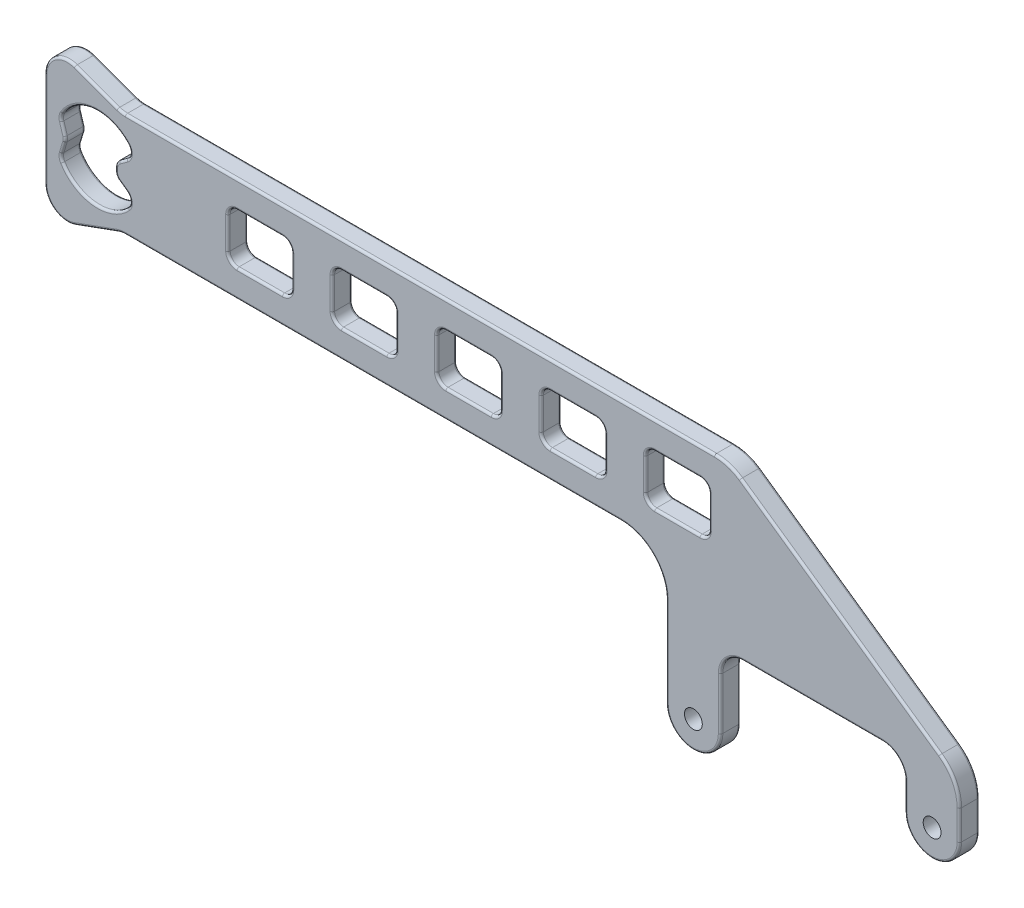
SolidWorks part; units mm, degrees
other "Markup1"
sketch "Sketch10" plane through (-231.7542, 109.3418, 2.54) normal (-0.196, 0.5701, 0.7978) x (0.8612, -0.289, 0.4181)
sketch "Sketch12" plane through (-223.9721, 110.3689, 5.588) normal (-0.196, 0.5701, 0.7978) x (0.8612, -0.289, 0.4181)
material "Alloy Steel"
ref_plane "Front Plane" through (0, 0, 0) normal (0, 0, 1) x (1, 0, 0)
ref_plane "Top Plane" through (0, 0, 0) normal (0, 1, 0) x (1, 0, 0)
ref_plane "Right Plane" through (0, 0, 0) normal (1, 0, 0) x (0, 0, -1)
sketch "Sketch1" plane through (0, 0, 0) normal (0, 0, 1) x (1, 0, 0)
  line L0 (-51.1821, 45.104) -> (-51.1821, 70.2222)
  line L1 (-225.0635, 110.882) -> (-225.0635, 84.1724)
  line L2 (15.625, 52.2091) -> (15.625, 59.6953)
  line L3 (-204.6342, 112.5152) -> (-216.5416, 116.8491)
  line L4 (24.515, 112.1322) -> (-202.4624, 112.1322)
  line L5 (-202.4624, 82.9222) -> (-63.8821, 82.9222)
  line L6 (-35.9421, 45.104) -> (-35.9421, 59.6953)
  line L7 (-29.5921, 66.0453) -> (9.275, 66.0453)
  line L8 (-204.6342, 82.5393) -> (-216.5416, 78.2053)
  line L9 (-203.5821, 112.1322) -> (-203.5821, 82.9222) construction
  line L10 (30.865, 52.2091) -> (30.865, 105.7822)
  circle A0 centre (-43.5621, 45.104) radius 2.5 construction
  circle A1 centre (-43.5621, 45.104) radius 2.5
  circle A2 centre (23.245, 52.2091) radius 2.5 construction
  circle A3 centre (23.245, 52.2091) radius 2.5
  circle A4 centre (-43.5621, 45.104) radius 7.62
  circle A5 centre (23.245, 52.2091) radius 7.62
  arc A6 (-51.1821, 70.2222) -> (-63.8821, 82.9222) centre (-63.8821, 70.2222) ccw
  arc A10 (30.865, 105.7822) -> (24.515, 112.1322) centre (24.515, 105.7822) ccw
  arc A11 (-202.4624, 112.1322) -> (-204.6342, 112.5152) centre (-202.4624, 118.4822) cw
  arc A14 (15.625, 59.6953) -> (9.275, 66.0453) centre (9.275, 59.6953) ccw
  arc A15 (-29.5921, 66.0453) -> (-35.9421, 59.6953) centre (-29.5921, 59.6953) ccw
  arc A16 (-202.4624, 82.9222) -> (-204.6342, 82.5393) centre (-202.4624, 76.5722) ccw
  arc A17 (-216.5416, 78.2053) -> (-225.0635, 84.1724) centre (-218.7135, 84.1724) cw
  arc A18 (-216.5416, 116.8491) -> (-225.0635, 110.882) centre (-218.7135, 110.882) ccw
  point P37 (32.653, 69.7785)
  point P40 (-225.0635, 119.9508)
  dimension "D1" = 15.24
  dimension "D2" = 12.7
  dimension "D5" = 20
  dimension "D6" = 22.86
  dimension "D7" = 139.7
  dimension "D8" = 6.35
  dimension "D3" = 6.35
  dimension "D4" = 29.21
  dimension "D10" = 6.35
  dimension "D9" = 20
sketch "Sketch9" plane through (0, 0, 0) normal (0, 0, 1) x (1, 0, 0)
  line L0 (-200.3986, 101.5627) -> (-206.3477, 98.901)
  line L1 (-230.8813, 109.1826) -> (-231.1891, 107.025)
  line L2 (-231.0352, 108.1038) -> (-31.7302, 79.671) construction
  line L3 (-204.7592, 110.0362) -> (-174.8282, 105.7663) construction
  line L4 (-190.5732, 97.9876) -> (-182.1974, 90.8738)
  line L5 (-182.2147, 103.3096) -> (-176.2656, 105.9713)
  line L6 (-178.6469, 115.7616) -> (-182.5307, 88.5377) construction
  line L20 (-200.4159, 113.9985) -> (-179.3276, 110.9901)
  line L21 (-204.7592, 110.0362) -> (-206.3477, 98.901)
  line L22 (-176.2656, 105.9713) -> (-177.8541, 94.8361)
  line L23 (-203.2857, 93.8822) -> (-182.1974, 90.8738)
  line L24 (-171.3421, 113.5062) -> (-175.2234, 86.2993) construction
  line L29 (-136.2614, 108.4187) -> (-140.1311, 81.293) construction
  line L34 (-99.6701, 103.0287) -> (-103.5282, 75.9843) construction
  line L39 (-62.2356, 97.6053) -> (-66.0821, 70.6423) construction
  line L44 (-204.7592, 110.0362) -> (-199.7917, 105.8172)
  line L45 (-200.4159, 113.9985) -> (-192.0401, 106.8847)
  line L46 (-179.3276, 110.9901) -> (-189.3585, 106.5022)
  line L47 (-203.2857, 93.8822) -> (-193.2548, 98.3701)
  line L48 (-182.8216, 99.0551) -> (-177.8541, 94.8361)
  line L49 (-163.7544, 100.6761) -> (-168.7219, 104.8952)
  line L50 (-164.3614, 96.4216) -> (-170.3105, 93.7599)
  line L51 (-157.2176, 93.2291) -> (-167.2484, 88.7411)
  line L52 (-146.1602, 85.7327) -> (-154.5359, 92.8465)
  line L53 (-146.7844, 93.9141) -> (-141.8169, 89.695)
  line L54 (-140.2283, 100.8303) -> (-146.1774, 98.1685)
  line L55 (-143.2904, 105.849) -> (-153.3213, 101.3611)
  line L56 (-164.3786, 108.8575) -> (-156.0029, 101.7437)
  line L57 (-146.1602, 85.7327) -> (-167.2484, 88.7411)
  line L58 (-140.2283, 100.8303) -> (-141.8169, 89.695)
  line L59 (-143.2904, 105.849) -> (-164.3786, 108.8575)
  line L60 (-168.7219, 104.8952) -> (-170.3105, 93.7599)
  line L61 (-133.1011, 83.8697) -> (-112.0129, 80.8612)
  line L62 (-120.3887, 87.9751) -> (-112.0129, 80.8612)
  line L63 (-133.1011, 83.8697) -> (-123.0703, 88.3576)
  line L64 (-134.5746, 100.0237) -> (-136.1632, 88.8884)
  line L65 (-134.5746, 100.0237) -> (-129.6071, 95.8046)
  line L66 (-130.2141, 91.5502) -> (-136.1632, 88.8884)
  line L67 (-112.6371, 89.0426) -> (-107.6696, 84.8235)
  line L68 (-106.081, 95.9588) -> (-107.6696, 84.8235)
  line L69 (-112.0301, 93.2971) -> (-106.081, 95.9588)
  line L70 (-109.1431, 100.9776) -> (-119.174, 96.4896)
  line L71 (-130.2313, 103.986) -> (-109.1431, 100.9776)
  line L72 (-130.2313, 103.986) -> (-121.8556, 96.8722)
  line L73 (-72.93, 75.2857) -> (-94.0183, 78.2941)
  line L74 (-72.93, 75.2857) -> (-81.3058, 82.3995)
  line L75 (-83.9874, 82.782) -> (-94.0183, 78.2941)
  line L76 (-91.1312, 85.9746) -> (-97.0803, 83.3129)
  line L77 (-95.4918, 94.4481) -> (-97.0803, 83.3129)
  line L78 (-73.5542, 83.4671) -> (-68.5867, 79.248)
  line L79 (-66.9982, 90.3832) -> (-68.5867, 79.248)
  line L80 (-66.9982, 90.3832) -> (-72.9473, 87.7215)
  line L81 (-70.0602, 95.402) -> (-80.0911, 90.9141)
  line L82 (-91.1485, 98.4105) -> (-82.7727, 91.2966)
  line L83 (-70.0602, 95.402) -> (-91.1485, 98.4105)
  line L84 (-90.5243, 90.2291) -> (-95.4918, 94.4481)
  line L85 (-55.322, 80.866) -> (-61.2711, 78.2043)
  line L86 (-59.6825, 89.3396) -> (-54.715, 85.1205)
  line L87 (-55.3392, 93.3019) -> (-46.9635, 86.1881)
  line L88 (-34.251, 90.2935) -> (-44.2818, 85.8055)
  line L89 (-37.138, 82.613) -> (-31.1889, 85.2747)
  line L90 (-37.745, 78.3585) -> (-32.7775, 74.1394)
  line L91 (-45.4965, 77.2909) -> (-37.1208, 70.1771)
  line L92 (-58.209, 73.1856) -> (-48.1781, 77.6735)
  line L93 (-58.209, 73.1856) -> (-37.1208, 70.1771)
  line L94 (-59.6825, 89.3396) -> (-61.2711, 78.2043)
  line L95 (-55.3392, 93.3019) -> (-34.251, 90.2935)
  line L96 (-31.1889, 85.2747) -> (-32.7775, 74.1394)
  arc A0 (-200.4159, 113.9985) -> (-204.7592, 110.0362) centre (-200.954, 110.2267) ccw
  arc A1 (-179.3276, 110.9901) -> (-176.2656, 105.9713) centre (-179.8657, 107.2183) cw
  arc A2 (-182.1974, 90.8738) -> (-177.8541, 94.8361) centre (-181.6594, 94.6456) ccw
  arc A3 (-203.2857, 93.8822) -> (-206.3477, 98.901) centre (-202.7476, 97.654) cw
  arc A20 (-190.5732, 97.9876) -> (-193.2548, 98.3701) centre (-192.2175, 96.0516) ccw
  arc A21 (-200.3986, 101.5627) -> (-199.7917, 105.8172) centre (-201.436, 103.8812) ccw
  arc A22 (-182.8216, 99.0551) -> (-182.2147, 103.3096) centre (-181.1773, 100.9911) cw
  arc A23 (-192.0401, 106.8847) -> (-189.3585, 106.5022) centre (-190.3958, 108.8207) ccw
  arc A24 (-164.3614, 96.4216) -> (-163.7544, 100.6761) centre (-165.3987, 98.7401) ccw
  arc A25 (-157.2176, 93.2291) -> (-154.5359, 92.8465) centre (-156.1802, 90.9105) cw
  arc A26 (-146.7844, 93.9141) -> (-146.1774, 98.1685) centre (-145.1401, 95.85) cw
  arc A27 (-153.3213, 101.3611) -> (-156.0029, 101.7437) centre (-154.3586, 103.6796) cw
  arc A28 (-146.1602, 85.7327) -> (-141.8169, 89.695) centre (-145.6221, 89.5045) ccw
  arc A29 (-143.2904, 105.849) -> (-140.2283, 100.8303) centre (-143.8285, 102.0772) cw
  arc A30 (-164.3786, 108.8575) -> (-168.7219, 104.8952) centre (-164.9167, 105.0857) ccw
  arc A31 (-167.2484, 88.7411) -> (-170.3105, 93.7599) centre (-166.7103, 92.5129) cw
  arc A32 (-112.0129, 80.8612) -> (-107.6696, 84.8235) centre (-111.4748, 84.633) ccw
  arc A33 (-120.3887, 87.9751) -> (-123.0703, 88.3576) centre (-122.0329, 86.0391) ccw
  arc A34 (-133.1011, 83.8697) -> (-136.1632, 88.8884) centre (-132.563, 87.6415) cw
  arc A35 (-130.2141, 91.5502) -> (-129.6071, 95.8046) centre (-131.2514, 93.8687) ccw
  arc A36 (-112.6371, 89.0426) -> (-112.0301, 93.2971) centre (-110.9928, 90.9786) cw
  arc A37 (-109.1431, 100.9776) -> (-106.081, 95.9588) centre (-109.6812, 97.2058) cw
  arc A38 (-121.8556, 96.8722) -> (-119.174, 96.4896) centre (-120.2113, 98.8082) ccw
  arc A39 (-130.2313, 103.986) -> (-134.5746, 100.0237) centre (-130.7694, 100.2142) ccw
  arc A40 (-72.93, 75.2857) -> (-68.5867, 79.248) centre (-72.392, 79.0575) ccw
  arc A41 (-83.9874, 82.782) -> (-81.3058, 82.3995) centre (-82.9501, 80.4635) cw
  arc A42 (-94.0183, 78.2941) -> (-97.0803, 83.3129) centre (-93.4802, 82.0659) cw
  arc A43 (-91.1312, 85.9746) -> (-90.5243, 90.2291) centre (-92.1686, 88.2931) ccw
  arc A44 (-73.5542, 83.4671) -> (-72.9473, 87.7215) centre (-71.9099, 85.403) cw
  arc A45 (-70.0602, 95.402) -> (-66.9982, 90.3832) centre (-70.5983, 91.6302) cw
  arc A46 (-80.0911, 90.9141) -> (-82.7727, 91.2966) centre (-81.1284, 93.2326) cw
  arc A47 (-91.1485, 98.4105) -> (-95.4918, 94.4481) centre (-91.6866, 94.6386) ccw
  arc A48 (-55.322, 80.866) -> (-54.715, 85.1205) centre (-56.3593, 83.1846) ccw
  arc A49 (-46.9635, 86.1881) -> (-44.2818, 85.8055) centre (-45.3192, 88.1241) ccw
  arc A50 (-37.745, 78.3585) -> (-37.138, 82.613) centre (-36.1007, 80.2945) cw
  arc A51 (-37.1208, 70.1771) -> (-32.7775, 74.1394) centre (-36.5827, 73.9489) ccw
  arc A52 (-45.4965, 77.2909) -> (-48.1781, 77.6735) centre (-47.1408, 75.355) ccw
  arc A53 (-58.209, 73.1856) -> (-61.2711, 78.2043) centre (-57.6709, 76.9574) cw
  arc A54 (-55.3392, 93.3019) -> (-59.6825, 89.3396) centre (-55.8773, 89.5301) ccw
  arc A55 (-34.251, 90.2935) -> (-31.1889, 85.2747) centre (-34.7891, 86.5216) cw
  point P23 (-177.0598, 100.4037)
  point P24 (-205.5535, 104.4686)
  point P85 (-196.7202, 103.2084)
  point P88 (-185.8931, 101.6639)
  dimension "D2" = 3.81
  dimension "D3" = 3.81
  dimension "D8" = 2.54
  dimension "D1" = 10.16
  dimension "D4" = 3.81
extrude "Boss-Extrude1" add sketch "Sketch1" along normal blind 5.588
sketch "Sketch11" plane through (0, 0, 5.588) normal (0, 0, 1) x (1, 0, 0)
  line L0 (-225.0635, 97.5272) -> (-181.5504, 97.5272) construction
  line L1 (-225.0635, 110.882) -> (-225.0635, 84.1724) construction
  line L10 (-202.2175, 93.6173) -> (-204.2535, 95.0676)
  line L11 (-202.2086, 101.4361) -> (-204.241, 99.981)
  line L12 (-205.3018, 97.9722) -> (-205.3191, 97.1929)
  line L13 (-200.1771, 112.1322) -> (-200.1771, 82.9222) construction
  line L14 (24.515, 112.1322) -> (-202.4624, 112.1322) construction
  line L15 (-202.4624, 82.9222) -> (-63.8821, 82.9222) construction
  line L16 (-219.3537, 96.78) -> (-220.3082, 93.6789)
  line L17 (-219.3537, 98.2744) -> (-220.3082, 101.3755)
  arc A5 (-201.8062, 105.2083) -> (-220.0549, 103.4358) centre (-210.2706, 97.5272) ccw
  arc A8 (-201.8114, 89.8404) -> (-202.2175, 93.6173) centre (-203.6912, 91.5486) ccw
  arc A9 (-204.2535, 95.0676) -> (-205.3191, 97.1929) centre (-202.7797, 97.1364) cw
  arc A10 (-204.241, 99.981) -> (-205.3018, 97.9722) centre (-202.7624, 97.9157) ccw
  arc A11 (-201.8062, 105.2083) -> (-202.2086, 101.4361) centre (-203.6872, 103.5014) cw
  arc A12 (-220.0549, 91.6186) -> (-201.8114, 89.8404) centre (-210.2706, 97.5272) ccw
  arc A13 (-219.3537, 98.2744) -> (-219.3537, 96.78) centre (-221.7813, 97.5272) cw
  arc A14 (-220.0549, 91.6186) -> (-220.3082, 93.6789) centre (-217.8806, 92.9316) cw
  arc A15 (-220.0549, 103.4358) -> (-220.3082, 101.3755) centre (-217.8806, 102.1228) ccw
  point P11 (-206.719, 87.8213)
  point P14 (-210.1269, 97.5272)
  point P20 (-200.1771, 92.1638)
  point P23 (-205.349, 95.8481)
  point P28 (-200.1771, 102.8906)
  point P33 (-219.1237, 97.5272)
  point P36 (-220.6182, 92.672)
  dimension "D1" = 22.86
  dimension "D2" = 6.35
  dimension "D3" = 2.54
  dimension "D4" = 5.08
  dimension "D5" = 2.54
extrude "Cut-Extrude1" cut sketch "Sketch11" against normal up to next
sketch "Sketch13" plane through (0, 0, 5.588) normal (0, 0, 1) x (1, 0, 0)
  line L0 (-12.6964, 112.1322) -> (30.865, 67.1311)
  line L1 (24.515, 112.1322) -> (-202.4624, 112.1322) construction
  line L2 (30.865, 52.2091) -> (30.865, 105.7822) construction
  line L3 (30.865, 67.1311) -> (30.865, 105.7822)
  line L4 (24.515, 112.1322) -> (-12.6964, 112.1322)
  arc A0 (30.865, 105.7822) -> (24.515, 112.1322) centre (24.515, 105.7822) ccw construction
  arc A1 (30.865, 105.7822) -> (24.515, 112.1322) centre (24.515, 105.7822) ccw
sketch "Sketch14" plane through (0, 0, 5.588) normal (0, 0, 1) x (1, 0, 0)
  line L0 (-173.7796, 101.9722) -> (-173.7796, 93.0822)
  line L1 (-171.2396, 90.5422) -> (-158.5396, 90.5422)
  line L2 (-155.9996, 93.0822) -> (-155.9996, 101.9722)
  line L3 (-158.5396, 104.5122) -> (-171.2396, 104.5122)
  line L12 (-202.4624, 82.9222) -> (-63.8821, 82.9222) construction
  line L13 (24.515, 112.1322) -> (-202.4624, 112.1322) construction
  line L14 (-144.5696, 101.9722) -> (-144.5696, 93.0822)
  line L15 (-142.0296, 90.5422) -> (-129.3296, 90.5422)
  line L16 (-126.7896, 93.0822) -> (-126.7896, 101.9722)
  line L17 (-129.3296, 104.5122) -> (-142.0296, 104.5122)
  line L18 (-115.3596, 101.9722) -> (-115.3596, 93.0822)
  line L19 (-112.8196, 90.5422) -> (-100.1196, 90.5422)
  line L20 (-97.5796, 93.0822) -> (-97.5796, 101.9722)
  line L21 (-100.1196, 104.5122) -> (-112.8196, 104.5122)
  line L30 (-86.1496, 101.9722) -> (-86.1496, 93.0822)
  line L31 (-83.6096, 90.5422) -> (-70.9096, 90.5422)
  line L32 (-68.3696, 93.0822) -> (-68.3696, 101.9722)
  line L33 (-70.9096, 104.5122) -> (-83.6096, 104.5122)
  line L34 (-56.9396, 101.9722) -> (-56.9396, 93.0822)
  line L35 (-54.3996, 90.5422) -> (-41.6996, 90.5422)
  line L36 (-39.1596, 93.0822) -> (-39.1596, 101.9722)
  line L37 (-41.6996, 104.5122) -> (-54.3996, 104.5122)
  arc A0 (-155.9996, 101.9722) -> (-158.5396, 104.5122) centre (-158.5396, 101.9722) ccw
  arc A1 (-155.9996, 93.0822) -> (-158.5396, 90.5422) centre (-158.5396, 93.0822) cw
  arc A2 (-171.2396, 90.5422) -> (-173.7796, 93.0822) centre (-171.2396, 93.0822) cw
  arc A3 (-171.2396, 104.5122) -> (-173.7796, 101.9722) centre (-171.2396, 101.9722) ccw
  arc A8 (-126.7896, 101.9722) -> (-129.3296, 104.5122) centre (-129.3296, 101.9722) ccw
  arc A9 (-126.7896, 93.0822) -> (-129.3296, 90.5422) centre (-129.3296, 93.0822) cw
  arc A10 (-142.0296, 90.5422) -> (-144.5696, 93.0822) centre (-142.0296, 93.0822) cw
  arc A11 (-142.0296, 104.5122) -> (-144.5696, 101.9722) centre (-142.0296, 101.9722) ccw
  arc A12 (-97.5796, 101.9722) -> (-100.1196, 104.5122) centre (-100.1196, 101.9722) ccw
  arc A13 (-97.5796, 93.0822) -> (-100.1196, 90.5422) centre (-100.1196, 93.0822) cw
  arc A14 (-112.8196, 90.5422) -> (-115.3596, 93.0822) centre (-112.8196, 93.0822) cw
  arc A15 (-112.8196, 104.5122) -> (-115.3596, 101.9722) centre (-112.8196, 101.9722) ccw
  arc A24 (-68.3696, 101.9722) -> (-70.9096, 104.5122) centre (-70.9096, 101.9722) ccw
  arc A25 (-68.3696, 93.0822) -> (-70.9096, 90.5422) centre (-70.9096, 93.0822) cw
  arc A26 (-83.6096, 90.5422) -> (-86.1496, 93.0822) centre (-83.6096, 93.0822) cw
  arc A27 (-83.6096, 104.5122) -> (-86.1496, 101.9722) centre (-83.6096, 101.9722) ccw
  arc A28 (-39.1596, 101.9722) -> (-41.6996, 104.5122) centre (-41.6996, 101.9722) ccw
  arc A29 (-39.1596, 93.0822) -> (-41.6996, 90.5422) centre (-41.6996, 93.0822) cw
  arc A30 (-54.3996, 90.5422) -> (-56.9396, 93.0822) centre (-54.3996, 93.0822) cw
  arc A31 (-54.3996, 104.5122) -> (-56.9396, 101.9722) centre (-54.3996, 101.9722) ccw
  point P28 (-155.6592, 95.109)
  dimension "D1" = 2.54
  dimension "D2" = 7.62
  dimension "D3" = 7.62
  dimension "D4" = 7.62
  dimension "D5" = 7.62
  dimension "D6" = 11.43
  dimension "D7" = 11.43
  dimension "D8" = 7.62
  dimension "D9" = 7.62
  dimension "D10" = 7.62
  dimension "D11" = 7.62
  dimension "D12" = 11.43
  dimension "D13" = 12.7
  dimension "D14" = 12.7
  dimension "D15" = 7.62
  dimension "D16" = 11.43
extrude "Cut-Extrude3" cut sketch "Sketch14" against normal up to next
sketch "Sketch17" plane through (0, 0, 5.588) normal (0, 0, 1) x (1, 0, 0)
  line L0 (-33.6457, 112.1322) -> (30.865, 67.1311)
  line L1 (24.515, 112.1322) -> (-202.4624, 112.1322) construction
  line L2 (30.865, 67.1311) -> (30.865, 105.7822) construction
  line L3 (30.865, 67.1311) -> (30.865, 105.7822)
  line L4 (24.515, 112.1322) -> (-33.6457, 112.1322)
  arc A0 (30.865, 105.7822) -> (24.515, 112.1322) centre (24.515, 105.7822) ccw construction
  arc A1 (30.865, 105.7822) -> (24.515, 112.1322) centre (24.515, 105.7822) ccw
extrude "Cut-Extrude5" cut sketch "Sketch17" against normal up to next
fillet "Fillet3" radius 12.7 2 edges at (30.865, 67.1311, 2.794) (-33.6457, 112.1322, 2.794)
fillet "Fillet5" radius 0.635 115 edges at (-203.5651, 112.2287, 0) (-222.3557, 116.0837, 0) (-222.3557, 78.9707, 0) (-210.5879, 80.3723, 0) (-203.5651, 82.8257, 0) (-133.1723, 82.9222, 0) (-54.9018, 79.2025, 0) (-35.9421, 52.3997, 0) (-34.0822, 64.1854, 0) (-10.1585, 66.0453, 0) (13.7651, 64.1854, 0) (15.625, 55.9522, 0) (23.245, 44.5891, 0) (30.865, 56.3574, 0) (29.4248, 66.3798, 0) (-2.4703, 90.385, 0) (-33.8294, 111.5478, 0) (-120.05, 112.1322, 0) (-211.3756, 108.9037, 0) (-201.1615, 103.232, 0) (-203.2248, 100.7086, 0) (-205.0085, 99.1018, 0) (-205.0503, 95.9979, 0) (-203.2355, 94.3425, 0) (-201.1658, 91.8201, 0) (-220.4017, 92.6217, 0) (-219.831, 95.2294, 0) (-219.2413, 97.5272, 0) (-219.831, 99.825, 0) (-126.7896, 97.5272, 0) (-127.5335, 91.2862, 0) (-135.6796, 90.5422, 0) (-143.8256, 91.2862, 0) (-143.8256, 103.7683, 0) (-135.6796, 104.5122, 0) (-127.5335, 103.7683, 0) (-156.7435, 91.2862, 0) (-164.8896, 90.5422, 0) (-173.7796, 97.5272, 0) (-173.0356, 103.7683, 0) (-164.8896, 104.5122, 0) (-155.9996, 97.5272, 0) (-98.3235, 103.7683, 0) (-98.3235, 91.2862, 0) (-106.4696, 90.5422, 0) (-114.6156, 91.2862, 0) (-115.3596, 97.5272, 0) (-69.1135, 103.7683, 0) (-68.3696, 97.5272, 0) (-85.4056, 91.2862, 0) (-86.1496, 97.5272, 0) (-85.4056, 103.7683, 0) (-77.2596, 104.5122, 0) (-39.9035, 103.7683, 0) (-39.1596, 97.5272, 0) (-48.0496, 90.5422, 0) (-56.1956, 91.2862, 0) (-56.9396, 97.5272, 0) (-56.1956, 103.7683, 0) (-220.4017, 92.6217, 5.588) (-211.3794, 86.1511, 5.588) (-201.1658, 91.8201, 5.588) (-205.0503, 95.9979, 5.588) (-205.3105, 97.5825, 5.588) (-205.0085, 99.1018, 5.588) (-203.2248, 100.7086, 5.588) (-201.1615, 103.232, 5.588) (-219.831, 99.825, 5.588) (-219.2413, 97.5272, 5.588) (-143.8256, 103.7683, 5.588) (-144.5696, 97.5272, 5.588) (-135.6796, 90.5422, 5.588) (-127.5335, 91.2862, 5.588) (-126.7896, 97.5272, 5.588) (-127.5335, 103.7683, 5.588) (-135.6796, 104.5122, 5.588) (-164.8896, 104.5122, 5.588) (-173.0356, 103.7683, 5.588) (-173.7796, 97.5272, 5.588) (-173.0356, 91.2862, 5.588) (-164.8896, 90.5422, 5.588) (-156.7435, 91.2862, 5.588) (-155.9996, 97.5272, 5.588) (-106.4696, 90.5422, 5.588) (-97.5796, 97.5272, 5.588) (-98.3235, 103.7683, 5.588) (-114.6156, 103.7683, 5.588) (-85.4056, 91.2862, 5.588) (-77.2596, 90.5422, 5.588) (-69.1135, 91.2862, 5.588) (-68.3696, 97.5272, 5.588) (-77.2596, 104.5122, 5.588) (-85.4056, 103.7683, 5.588) (-56.9396, 97.5272, 5.588) (-56.1956, 91.2862, 5.588) (-39.9035, 91.2862, 5.588) (-39.1596, 97.5272, 5.588) (-39.9035, 103.7683, 5.588) (-48.0496, 104.5122, 5.588) (-56.1956, 103.7683, 5.588) (29.4248, 66.3798, 5.588) (30.865, 56.3574, 5.588) (-10.1585, 66.0453, 5.588) (-35.9421, 52.3997, 5.588) (-54.9018, 79.2025, 5.588) (-133.1723, 82.9222, 5.588) (-210.5879, 80.3723, 5.588) (-222.3557, 78.9707, 5.588) (-225.0635, 97.5272, 5.588) (-222.3557, 116.0837, 5.588) (-210.5879, 114.6821, 5.588) (-203.5651, 112.2287, 5.588) (-120.05, 112.1322, 5.588) (-33.8294, 111.5478, 5.588) (-2.4703, 90.385, 5.588)
